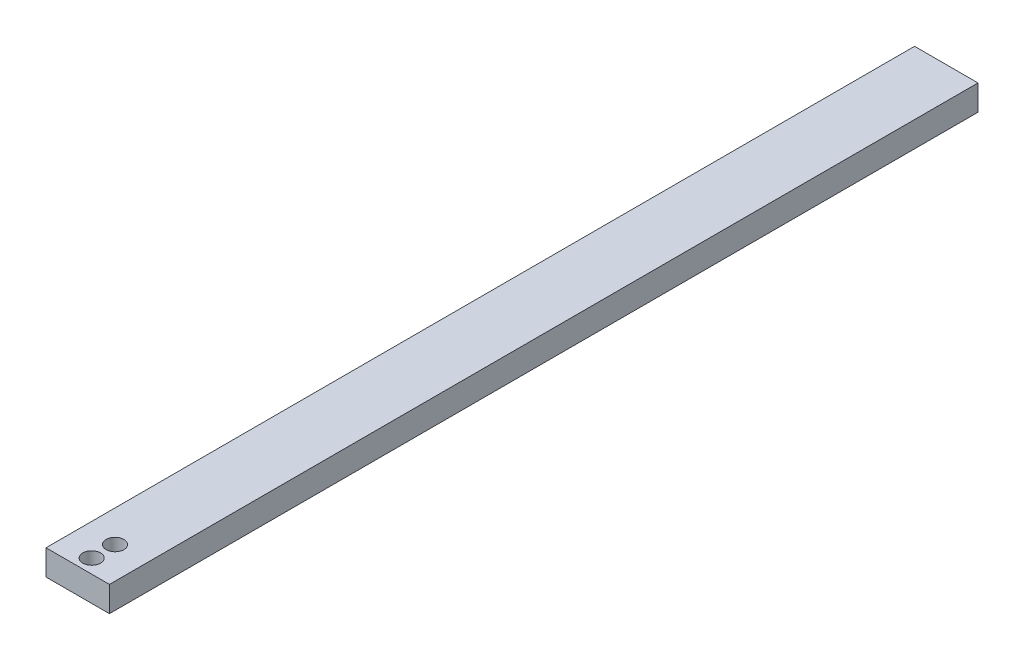
SolidWorks part; units mm, degrees
material "AA356.0-F"
ref_plane "Front Plane" through (0, 0, 0) normal (0, 0, 1) x (1, 0, 0)
ref_plane "Top Plane" through (0, 0, 0) normal (0, 1, 0) x (1, 0, 0)
ref_plane "Right Plane" through (0, 0, 0) normal (1, 0, 0) x (0, 0, -1)
sketch "Sketch2" plane through (0, 0, 0) normal (0, 0, 1) x (1, 0, 0)
  line L1 (-82.2086, 28.3742) -> (-32.2086, 28.3742)
  line L2 (-82.2086, 28.3742) -> (-82.2086, 8.3742)
  line L3 (-82.2086, 8.3742) -> (-32.2086, 8.3742)
  line L4 (-32.2086, 28.3742) -> (-32.2086, 8.3742)
  dimension "D1" = 50
  dimension "D2" = 20
extrude "Boss-Extrude1" add sketch "Sketch2" along normal blind 684.5
sketch "Sketch3" plane through (0, 28.3742, 0) normal (0, 1, 0) x (1, 0, 0)
  line L0 (-32.2086, -684.5) -> (-82.2086, -684.5) construction
  circle A0 centre (-57.2086, -673.5) radius 7
  circle A1 centre (-57.2086, -655.1) radius 7
  point P6 (-57.2086, -684.5)
  dimension "D1" = 18.4
  dimension "D2" = 11
extrude "Cut-Extrude1" cut sketch "Sketch3" against normal through all and the other way through all
sketch "Sketch4" plane through (0, 0, 0) normal (0, 0, -1) x (-1, 0, 0)
  line L0 (32.2086, 8.3742) -> (32.2086, 28.3742) construction
  line L1 (32.2086, 28.3742) -> (82.2086, 28.3742) construction
  circle A0 centre (57.2086, 18.3742) radius 7
  point P4 (32.2086, 18.3742)
  point P7 (57.2086, 28.3742)
extrude "Cut-Extrude2" cut sketch "Sketch4" against normal blind 14
